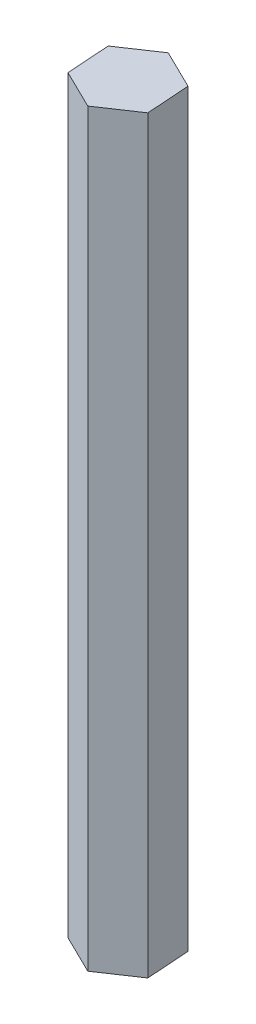
SolidWorks part; units mm, degrees
ref_plane "Front Plane" through (0, 0, 0) normal (0, 0, 1) x (1, 0, 0)
ref_plane "Top Plane" through (0, 0, 0) normal (0, 1, 0) x (1, 0, 0)
ref_plane "Right Plane" through (0, 0, 0) normal (1, 0, 0) x (0, 0, -1)
sketch "Sketch1" plane through (0, 0, 0) normal (0, 1, 0) x (1, 0, 0)
  line L1 (6.0869, 4.0882) -> (-0.497, 7.3155)
  line L2 (-0.497, 7.3155) -> (-6.5839, 3.2273)
  line L3 (-6.5839, 3.2273) -> (-6.0869, -4.0882)
  line L4 (-6.0869, -4.0882) -> (0.497, -7.3155)
  line L5 (0.497, -7.3155) -> (6.5839, -3.2273)
  line L6 (6.5839, -3.2273) -> (6.0869, 4.0882)
  circle A0 centre (0, 0) radius 6.35 construction
  dimension "D1" = 12.7
extrude "Boss-Extrude1" add sketch "Sketch1" along normal mid plane 127
